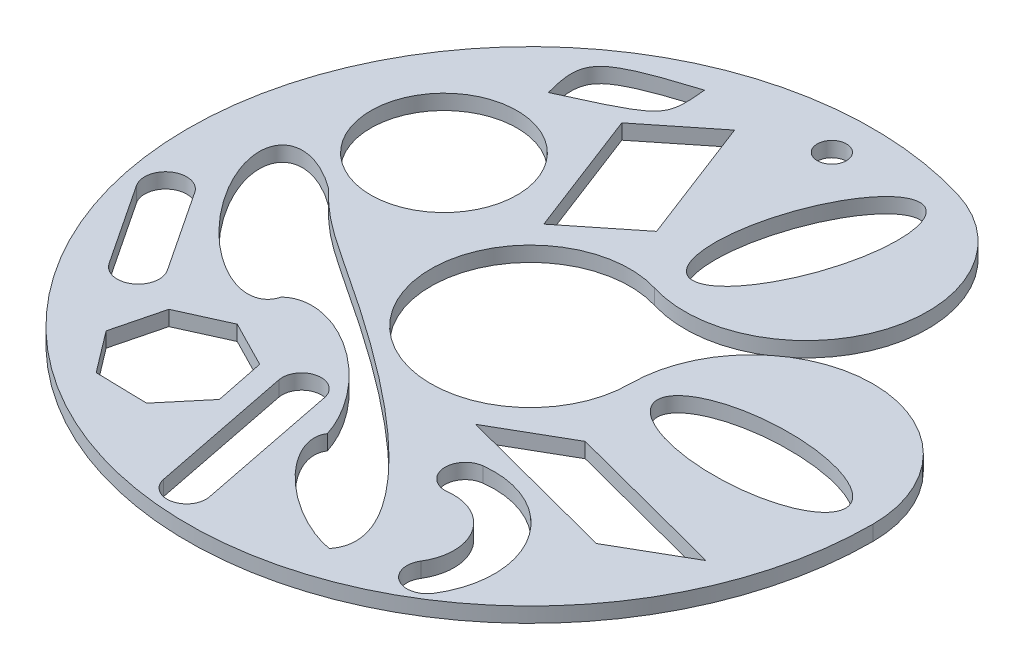
SolidWorks part; units mm, degrees
ref_plane "Front" through (0, 0, 0) normal (0, 0, 1) x (1, 0, 0)
ref_plane "Top" through (0, 0, 0) normal (0, 1, 0) x (1, 0, 0)
ref_plane "Right" through (0, 0, 0) normal (1, 0, 0) x (0, 0, -1)
sketch "Sketch3" plane through (0, 0, 0) normal (0, 1, 0) x (1, 0, 0)
  line L0 (-11.4701, 45.9645) -> (-3.2352, 24.5578)
  line L1 (-11.4701, 45.9645) -> (-22.0579, 37.4984)
  line L2 (-3.2352, 24.5578) -> (-13.8229, 16.0917)
  line L3 (-22.0579, 37.4984) -> (-13.8229, 16.0917)
  line L4 (21.4697, -12.2054) -> (49.1182, -19.439)
  line L5 (21.4697, -12.2054) -> (9.7055, -18.9698)
  line L6 (49.1182, -19.439) -> (37.354, -26.2034)
  line L7 (9.7055, -18.9698) -> (37.354, -26.2034)
  line L8 (15.511, -49.5078) -> (25.653, -37.0783) construction
  line L9 (25.653, -37.0783) -> (-27.8051, -3.4402) construction
  line L10 (-27.8051, -3.4402) -> (-27.8051, -6.5109) construction
  line L11 (-27.8051, -6.5109) -> (-37.2242, 3.1104) construction
  line L12 (-41.8205, -24.4499) -> (-50.9298, -10.7023) construction
  line L13 (-17.3155, -28.4247) -> (-25.0864, -24.4499)
  line L14 (-25.0864, -24.4499) -> (-33.0391, -28.0471)
  line L15 (-33.0391, -28.0471) -> (-35.1851, -36.5077)
  line L16 (-35.1851, -36.5077) -> (-29.9083, -43.4605)
  line L17 (-29.9083, -43.4605) -> (-21.1824, -43.67)
  line L18 (-21.1824, -43.67) -> (-15.578, -36.9785)
  line L19 (-15.578, -36.9785) -> (-17.3155, -28.4247)
  line L20 (-44.7817, -26.412) -> (-53.8911, -12.6644)
  line L21 (-38.8592, -22.4877) -> (-47.9686, -8.7401)
  line L22 (-10.1926, -28.4529) -> (-5.3885, -52.7051) construction
  line L23 (-6.9661, -27.8138) -> (-2.162, -52.066)
  line L24 (-13.4192, -29.0921) -> (-8.6151, -53.3443)
  arc A0 (10.8819, 35.7338) -> (37.354, 0) centre (0, 0) ccw construction
  arc A1 (16.8634, 55.3759) -> (57.8866, 0) centre (0, 0) ccw
  arc A2 (4.9004, 16.0917) -> (16.8213, 0) centre (0, 0) ccw
  arc A3 (4.9004, 16.0917) -> (16.8634, 55.3759) centre (10.8819, 35.7338) ccw
  arc A4 (57.8866, 0) -> (16.8213, 0) centre (37.354, 0) ccw
  circle A5 centre (-32.6873, 18.0793) radius 12.3589
  circle A6 centre (-25.3278, -34.5055) radius 9.0624 construction
  circle A7 centre (0, 50.9349) radius 2.4641
  arc A8 (-44.7817, -26.412) -> (-38.8592, -22.4877) centre (-41.8205, -24.4499) ccw
  arc A9 (-47.9686, -8.7401) -> (-53.8911, -12.6644) centre (-50.9298, -10.7023) ccw
  arc A10 (-6.9661, -27.8138) -> (-13.4192, -29.0921) centre (-10.1926, -28.4529) ccw
  arc A11 (-8.6151, -53.3443) -> (-2.162, -52.066) centre (-5.3885, -52.7051) ccw
  arc A12 (16.8213, -27.8138) -> (27.9898, -45.4211) centre (18.2204, -39.2722) cw construction
  arc A13 (30.8869, -47.2445) -> (16.4064, -24.4159) centre (18.2204, -39.2722) ccw
  arc A14 (25.0928, -43.5977) -> (17.2362, -31.2117) centre (18.2204, -39.2722) ccw
  arc A15 (25.0928, -43.5977) -> (30.8869, -47.2445) centre (27.9898, -45.4211) ccw
  arc A16 (16.4064, -24.4159) -> (17.2362, -31.2117) centre (16.8213, -27.8138) ccw
  ellipse E0 centre (10.8819, 35.7338) end of major axis (6.2527, 20.5327) minor radius 6.2527
  ellipse E1 centre (37.354, 0) end of major axis (21.4697, 0) minor radius 6.3233
  ellipse E2 centre (-36.8149, -6.3233) end of major axis (-47.3509, 5.7204) minor radius 6.6507 (-37.2242, 3.1104) -> (-25.3278, -16.7715) ccw
  ellipse E3 centre (-13.8229, -28.6753) end of major axis (-25.3278, -16.7715) minor radius 8.3893 (-1.454, -32.8681) -> (-25.3278, -16.7715) ccw
  ellipse E4 centre (9.7055, -40.579) end of major axis (-1.454, -32.8681) minor radius 5.8855 (15.511, -49.5078) -> (-1.454, -32.8681) cw
  conic Q0 (-32.6873, 35.7338) -> (-19.8553, 49.2689) control (-35.1851, 44.509) rho 0.669217
  conic Q1 (-32.6873, 35.7338) -> (-19.8553, 49.2689) control (-19.0003, 41.8759) rho 0.734241
  spline S0 degree 4 poles (15.511, -49.5078) (25.653, -37.0783) (-27.8051, -3.4402) (-27.8051, -6.5109) (-37.2242, 3.1104) knots 0 0 0 0 0 1 1 1 1 1
  point P4 (-30.015, -22.2355)
  point P72 (-46.3751, -17.5761)
  point P79 (-7.7906, -40.579)
  point P87 (27.9682, -33.089)
extrude "Boss-Extrude3" add sketch "Sketch3" along normal blind 2.54
